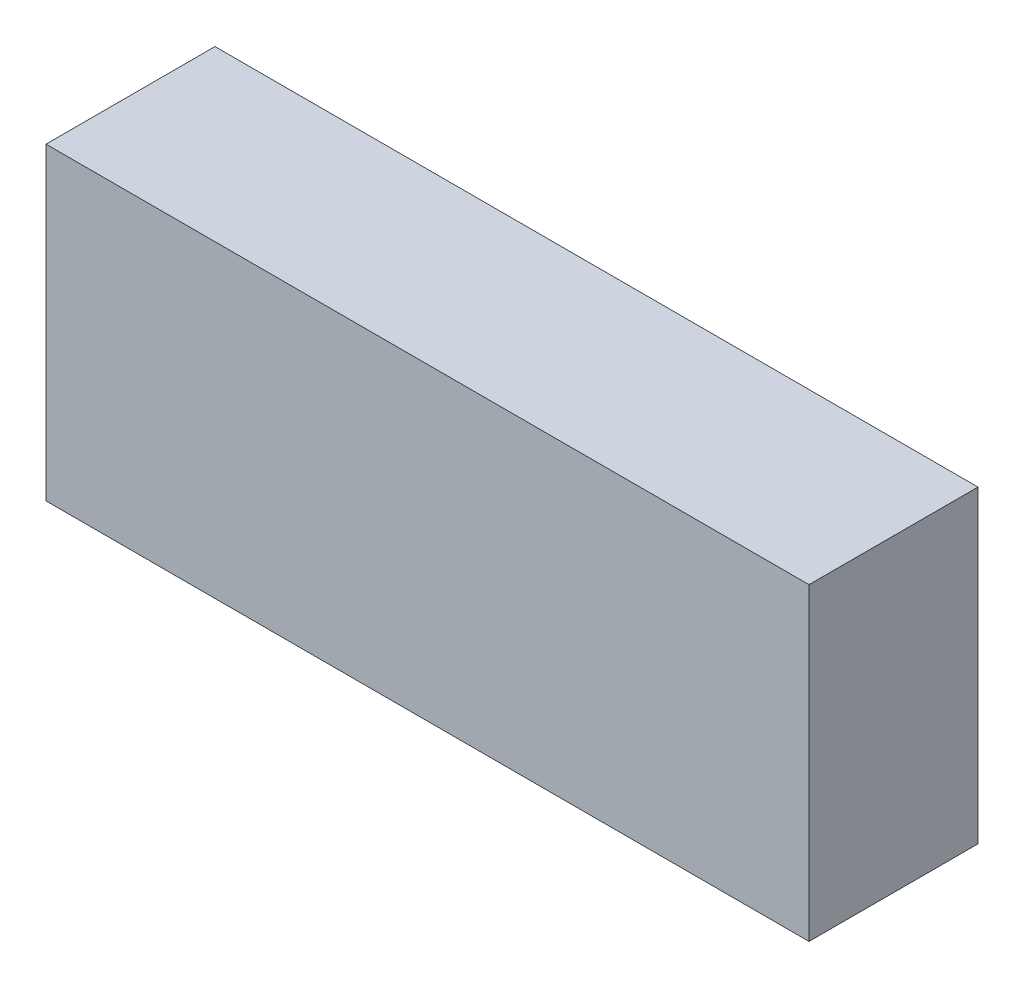
SolidWorks part; units mm, degrees
ref_plane "Alzado" through (0, 0, 0) normal (0, 0, 1) x (1, 0, 0)
ref_plane "Planta" through (0, 0, 0) normal (0, 1, 0) x (1, 0, 0)
ref_plane "Vista lateral" through (0, 0, 0) normal (1, 0, 0) x (0, 0, -1)
sketch "Croquis1" plane through (0, 0, 0) normal (0, 0, 1) x (1, 0, 0)
  line L1 (-12.1, -4.9) -> (12.1, -4.9)
  line L2 (-12.1, -4.9) -> (-12.1, 4.9)
  line L3 (-12.1, 4.9) -> (12.1, 4.9)
  line L4 (12.1, -4.9) -> (12.1, 4.9)
  line L5 (-12.1, -4.9) -> (12.1, 4.9) construction
  line L6 (-12.1, 4.9) -> (12.1, -4.9) construction
  point P0 (0, 0)
  dimension "D1" = 24.2
  dimension "D2" = 9.8
extrude "Saliente-Extruir1" add sketch "Croquis1" along normal blind 5.36
